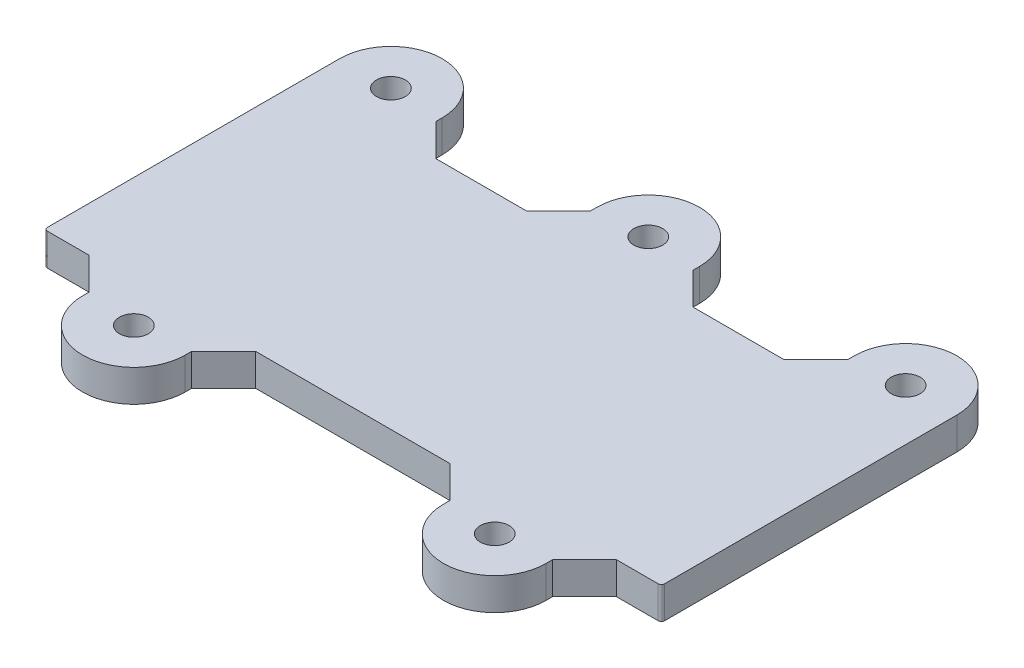
SolidWorks part; units mm, degrees
ref_plane "Front Plane" through (0, 0, 0) normal (0, 0, 1) x (1, 0, 0)
ref_plane "Top Plane" through (0, 0, 0) normal (0, 1, 0) x (1, 0, 0)
ref_plane "Right Plane" through (0, 0, 0) normal (1, 0, 0) x (0, 0, -1)
sketch "Sketch1" plane through (0, 0, 0) normal (0, 1, 0) x (1, 0, 0)
  line L0 (48.15, -20.05) -> (48.15, 20.05) construction
  line L1 (48.15, -20.05) -> (-48.15, -20.05) construction
  line L2 (48.15, 20.05) -> (-48.15, 20.05) construction
  line L3 (-48.15, -20.05) -> (-48.15, 20.05) construction
  line L4 (48.15, -20.05) -> (48.15, 20.05)
  line L5 (48.15, -20.05) -> (36.15, -20.05)
  line L6 (32.15, 20.05) -> (8, 20.05)
  line L7 (-48.15, -20.05) -> (-48.15, 20.05)
  line L8 (-48.15, 20.05) -> (-48.15, 26.05)
  line L9 (-8, 20.05) -> (-32.15, 20.05)
  line L10 (-32.15, 26.05) -> (-32.15, 20.05)
  line L11 (-8, 26.05) -> (-8, 20.05)
  line L12 (8, 26.05) -> (8, 20.05)
  line L13 (-20.15, -26.05) -> (-20.15, -20.05)
  line L14 (-36.15, -26.05) -> (-36.15, -20.05)
  line L15 (-36.15, -20.05) -> (-48.15, -20.05)
  line L16 (0, 0) -> (0, -20.05) construction
  line L17 (32.15, 26.05) -> (32.15, 20.05)
  line L18 (48.15, 20.05) -> (48.15, 26.05)
  line L19 (36.15, -26.05) -> (36.15, -20.05)
  line L20 (20.15, -26.05) -> (20.15, -20.05)
  line L21 (20.15, -20.05) -> (-20.15, -20.05)
  circle A0 centre (-28.15, -26.05) radius 2.8 construction
  circle A1 centre (-40.15, 26.05) radius 2.8 construction
  circle A2 centre (0, 26.05) radius 2.8 construction
  circle A3 centre (-28.15, -26.05) radius 2.8 construction
  circle A4 centre (-40.15, 26.05) radius 2.8 construction
  circle A5 centre (0, 26.05) radius 2.8 construction
  arc A6 (-32.15, 26.05) -> (-48.15, 26.05) centre (-40.15, 26.05) ccw
  arc A7 (8, 26.05) -> (-8, 26.05) centre (0, 26.05) ccw
  arc A8 (-36.15, -26.05) -> (-20.15, -26.05) centre (-28.15, -26.05) ccw
  arc A9 (32.15, 26.05) -> (48.15, 26.05) centre (40.15, 26.05) cw
  circle A10 centre (40.15, 26.05) radius 2.8 construction
  arc A11 (36.15, -26.05) -> (20.15, -26.05) centre (28.15, -26.05) cw
  circle A12 centre (28.15, -26.05) radius 2.8 construction
extrude "Boss-Extrude1" add sketch "Sketch1" along normal blind 5
chamfer "Chamfer1" distance 5 angle 45 8 edges at (-32.15, 2.5, -20.05) (-8, 2.5, -20.05) (8, 2.5, -20.05) (32.15, 2.5, -20.05) (36.15, 2.5, 20.05) (20.15, 2.5, 20.05) (-20.15, 2.5, 20.05) (-36.15, 2.5, 20.05)
hole_wizard "M4 Clearance Hole1" positions "3DSketch1" profile "Sketch2" hole size "M4" standard "ANSI Metric" end condition through all
sketch3d "3DSketch1"
  point P0 (-40.15, 0, -26.05)
  point P3 (0, 0, -26.05)
  point P6 (40.15, 0, -26.05)
  point P9 (28.15, 0, 26.05)
  point P12 (-28.15, 0, 26.05)
  point P16 (-40.15, 0, -26.05)
  point P18 (40.15, 0, -26.05)
  point P20 (0, 0, -26.05)
  point P22 (-40.15, 0, -26.05)
  point P24 (-28.15, 0, 26.05)
  point P26 (28.15, 0, 26.05)
sketch "Sketch2" plane through (28.15, 0, 26.05) normal (1, 0, 0) x (0, 0, -1)
  line L0 (0, 0) -> (0, 5)
  line L1 (0, 5) -> (2.25, 5)
  line L2 (2.25, 5) -> (2.25, 0)
  line L5 (2.25, 0) -> (0, 0)
  line L11 (0, -6.35) -> (0, 107.95) construction
  dimension "Thru Hole Dia." = 4.5
  dimension "Thru Hole Depth" = 5
fillet "Fillet1" radius 0.5 2 edges at (-48.15, 2.5, 20.05) (48.15, 2.5, 20.05)
